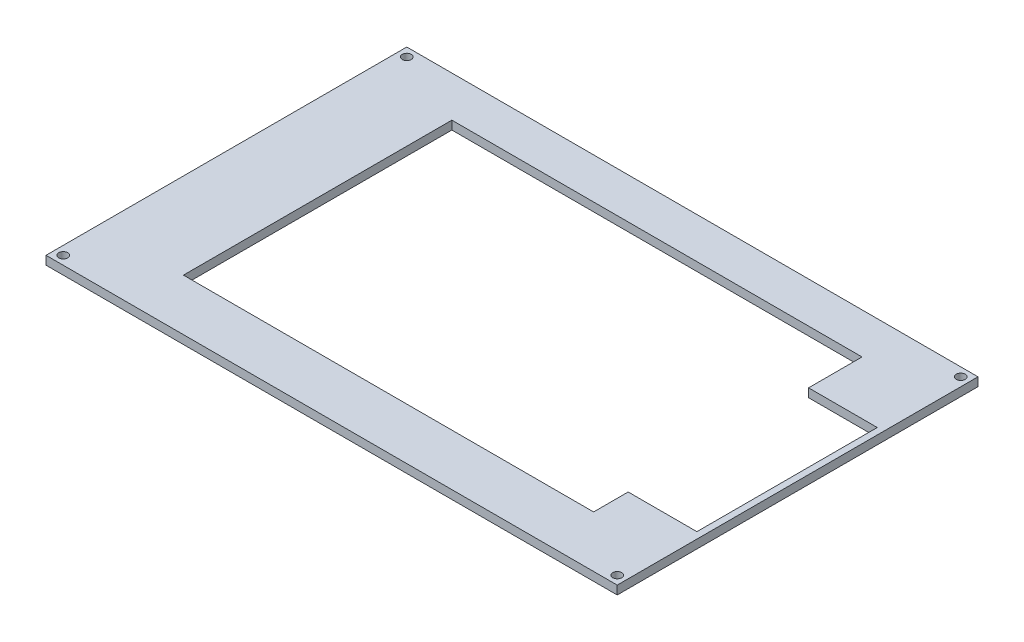
SolidWorks part; units mm, degrees
ref_plane "前视基准面" through (0, 0, 0) normal (0, 0, 1) x (1, 0, 0)
ref_plane "上视基准面" through (0, 0, 0) normal (0, 1, 0) x (1, 0, 0)
ref_plane "右视基准面" through (0, 0, 0) normal (1, 0, 0) x (0, 0, -1)
sketch "草图1" plane through (0, 0, 0) normal (0, 1, 0) x (1, 0, 0)
  line L1 (0, 0) -> (133, 0)
  line L2 (0, 0) -> (0, -84)
  line L3 (0, -84) -> (133, -84)
  line L4 (133, 0) -> (133, -84)
  line L5 (2, -2) -> (131, -2) construction
  line L6 (2, -2) -> (2, -82) construction
  line L7 (2, -82) -> (131, -82) construction
  line L8 (131, -2) -> (131, -82) construction
  line L9 (20, -9.5) -> (115.5, -9.5)
  line L10 (20, -9.5) -> (20, -72)
  line L11 (20, -72) -> (115.5, -72)
  line L12 (115.5, -9.5) -> (115.5, -72)
  line L13 (115.5, -63.95) -> (131.5, -63.95)
  line L14 (115.5, -63.95) -> (115.5, -21.95)
  line L15 (115.5, -21.95) -> (131.5, -21.95)
  line L16 (131.5, -63.95) -> (131.5, -21.95)
  circle A0 centre (2, -2) radius 1.05
  circle A1 centre (131, -2) radius 1.05
  circle A2 centre (2, -82) radius 1.05
  circle A3 centre (131, -82) radius 1.05
  dimension "D7" = 2.1
  dimension "D8" = 2.1
  dimension "D9" = 2.1
  dimension "D10" = 2.1
  dimension "D1" = 133
  dimension "D2" = 84
  dimension "D3" = 2
  dimension "D4" = 2
  dimension "D5" = 2
  dimension "D6" = 2
  dimension "D11" = 95.5
  dimension "D12" = 62.5
  dimension "D13" = 20
  dimension "D14" = 12
  dimension "D15" = 12.45
  dimension "D16" = 42
  dimension "D17" = 16
extrude "凸台-拉伸1" add sketch "草图1" along normal blind 2 contours L4 L1 L2 L3 A3 A2 A1 A0 L16 L13 L12 L11 L10 L9 L15
